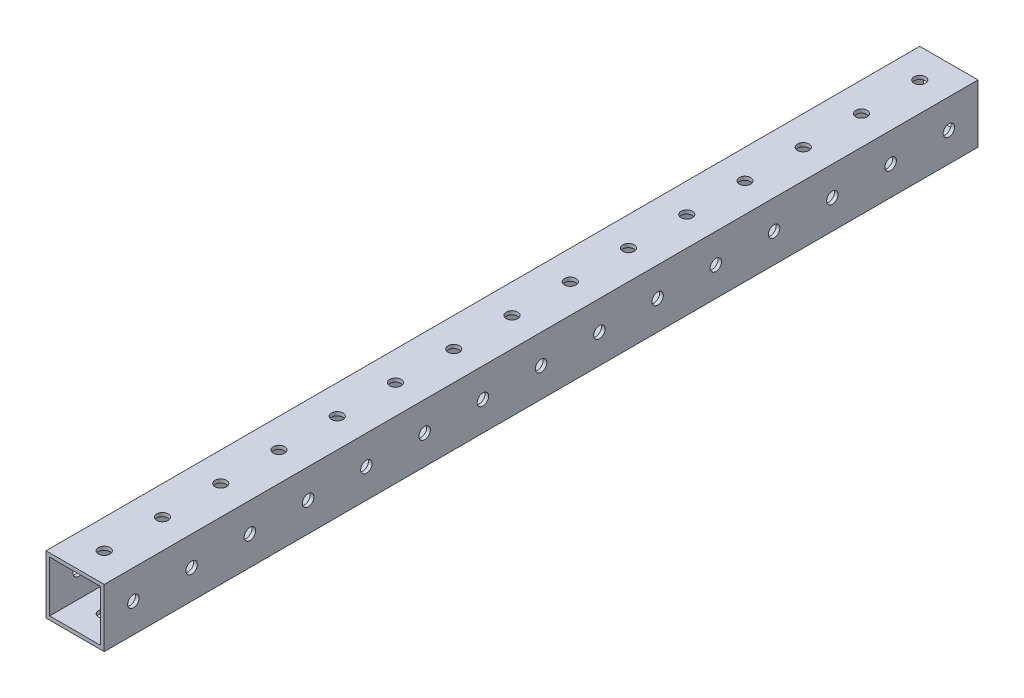
SolidWorks part; units mm, degrees
material "6061-T6 (SS)"
ref_plane "Front Plane" through (0, 0, 0) normal (0, 0, 1) x (1, 0, 0)
ref_plane "Top Plane" through (0, 0, 0) normal (0, 1, 0) x (1, 0, 0)
ref_plane "Right Plane" through (0, 0, 0) normal (1, 0, 0) x (0, 0, -1)
sketch "Sketch1" plane through (0, 0, 0) normal (0, 0, 1) x (1, 0, 0)
  line L1 (0, 0) -> (25.4, 0)
  line L2 (0, 0) -> (0, 25.4)
  line L3 (0, 25.4) -> (25.4, 25.4)
  line L4 (25.4, 0) -> (25.4, 25.4)
  dimension "D1" = 25.4
  dimension "D2" = 25.4
extrude "Boss-Extrude1" add sketch "Sketch1" against normal blind 381
shell "Shell1" thickness 1.5875
sketch "Sketch2" plane through (25.4, 0, 0) normal (1, 0, 0) x (0, 0, -1)
  line L0 (381, 25.4) -> (0, 25.4) construction
  line L1 (0, 0) -> (0, 25.4) construction
  circle A0 centre (12.7, 12.7) radius 2.4892
  circle A1 centre (38.1, 12.7) radius 2.4892
  circle A2 centre (63.5, 12.7) radius 2.4892
  circle A3 centre (88.9, 12.7) radius 2.4892
  circle A4 centre (114.3, 12.7) radius 2.4892
  circle A5 centre (139.7, 12.7) radius 2.4892
  circle A6 centre (165.1, 12.7) radius 2.4892
  circle A7 centre (190.5, 12.7) radius 2.4892
  circle A8 centre (215.9, 12.7) radius 2.4892
  circle A9 centre (241.3, 12.7) radius 2.4892
  circle A10 centre (266.7, 12.7) radius 2.4892
  circle A11 centre (292.1, 12.7) radius 2.4892
  circle A12 centre (317.5, 12.7) radius 2.4892
  circle A13 centre (342.9, 12.7) radius 2.4892
  circle A14 centre (368.3, 12.7) radius 2.4892
  dimension "D1" = 4.9784
  dimension "D2" = 12.7
  dimension "D3" = 12.7
  dimension "D4" = 15
extrude "Cut-Extrude1" cut sketch "Sketch2" against normal through all
sketch "Sketch3" plane through (0, 25.4, 0) normal (0, 1, 0) x (1, 0, 0)
  line L0 (25.4, 0) -> (0, 0) construction
  line L1 (25.4, 381) -> (25.4, 0) construction
  circle A0 centre (12.7, 12.7) radius 2.4892
  circle A1 centre (12.7, 38.1) radius 2.4892
  circle A2 centre (12.7, 63.5) radius 2.4892
  circle A3 centre (12.7, 88.9) radius 2.4892
  circle A4 centre (12.7, 114.3) radius 2.4892
  circle A5 centre (12.7, 139.7) radius 2.4892
  circle A6 centre (12.7, 165.1) radius 2.4892
  circle A7 centre (12.7, 190.5) radius 2.4892
  circle A8 centre (12.7, 215.9) radius 2.4892
  circle A9 centre (12.7, 241.3) radius 2.4892
  circle A10 centre (12.7, 266.7) radius 2.4892
  circle A11 centre (12.7, 292.1) radius 2.4892
  circle A12 centre (12.7, 317.5) radius 2.4892
  circle A13 centre (12.7, 342.9) radius 2.4892
  circle A14 centre (12.7, 368.3) radius 2.4892
  dimension "D1" = 4.9784
  dimension "D2" = 12.7
  dimension "D3" = 12.7
  dimension "D4" = 15
extrude "Cut-Extrude2" cut sketch "Sketch3" against normal through all
